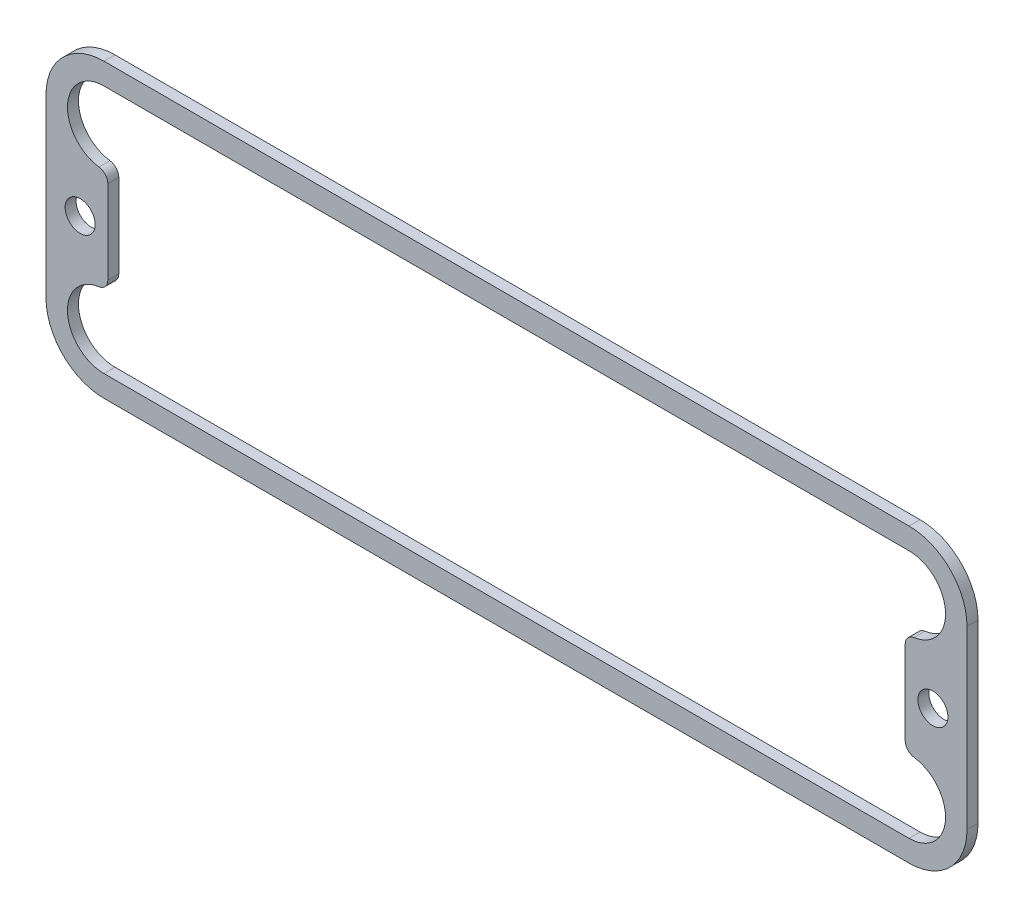
SolidWorks part; units mm, degrees
ref_plane "Front Plane" through (0, 0, 0) normal (0, 0, 1) x (1, 0, 0)
ref_plane "Top Plane" through (0, 0, 0) normal (0, 1, 0) x (1, 0, 0)
ref_plane "Right Plane" through (0, 0, 0) normal (1, 0, 0) x (0, 0, -1)
sketch "Sketch2" plane through (0, 0, 0.635) normal (0, 0, 1) x (1, 0, 0)
  line L12 (23.8125, 8.636) -> (-23.8125, 8.636)
  line L13 (-27.2415, 5.207) -> (-27.2415, -5.207)
  line L14 (-23.8125, -8.636) -> (23.8125, -8.636)
  line L15 (27.2415, -5.207) -> (27.2415, 5.207)
  line L24 (23.5855, -2.4705) -> (23.5855, 2.4705)
  line L25 (23.8125, 7.366) -> (-23.8125, 7.366)
  line L26 (-23.5855, 2.4705) -> (-23.5855, -2.4705)
  line L27 (-23.8125, -7.366) -> (23.8125, -7.366)
  arc A12 (-23.8125, 8.636) -> (-27.2415, 5.207) centre (-23.8125, 5.207) ccw
  arc A13 (-27.2415, -5.207) -> (-23.8125, -8.636) centre (-23.8125, -5.207) ccw
  arc A14 (23.8125, -8.636) -> (27.2415, -5.207) centre (23.8125, -5.207) ccw
  arc A15 (27.2415, 5.207) -> (23.8125, 8.636) centre (23.8125, 5.207) ccw
  circle A20 centre (-25.223, 0) radius 0.889
  circle A21 centre (25.223, 0) radius 0.889
  arc A36 (23.8125, -7.366) -> (24.1066, -3.0681) centre (23.8125, -5.207) ccw
  arc A37 (23.5855, -2.4705) -> (24.1066, -3.0681) centre (24.1887, -2.4705) ccw
  arc A38 (24.1066, 3.0681) -> (23.5855, 2.4705) centre (24.1887, 2.4705) ccw
  arc A39 (24.1066, 3.0681) -> (23.8125, 7.366) centre (23.8125, 5.207) ccw
  arc A40 (-23.8125, 7.366) -> (-24.1066, 3.0681) centre (-23.8125, 5.207) ccw
  arc A41 (-23.5855, 2.4705) -> (-24.1066, 3.0681) centre (-24.1887, 2.4705) ccw
  arc A42 (-24.1066, -3.0681) -> (-23.5855, -2.4705) centre (-24.1887, -2.4705) ccw
  arc A43 (-24.1066, -3.0681) -> (-23.8125, -7.366) centre (-23.8125, -5.207) ccw
  dimension "D3" = 1.778
extrude "Boss-Extrude1" add sketch "Sketch2" along normal blind 0.65
